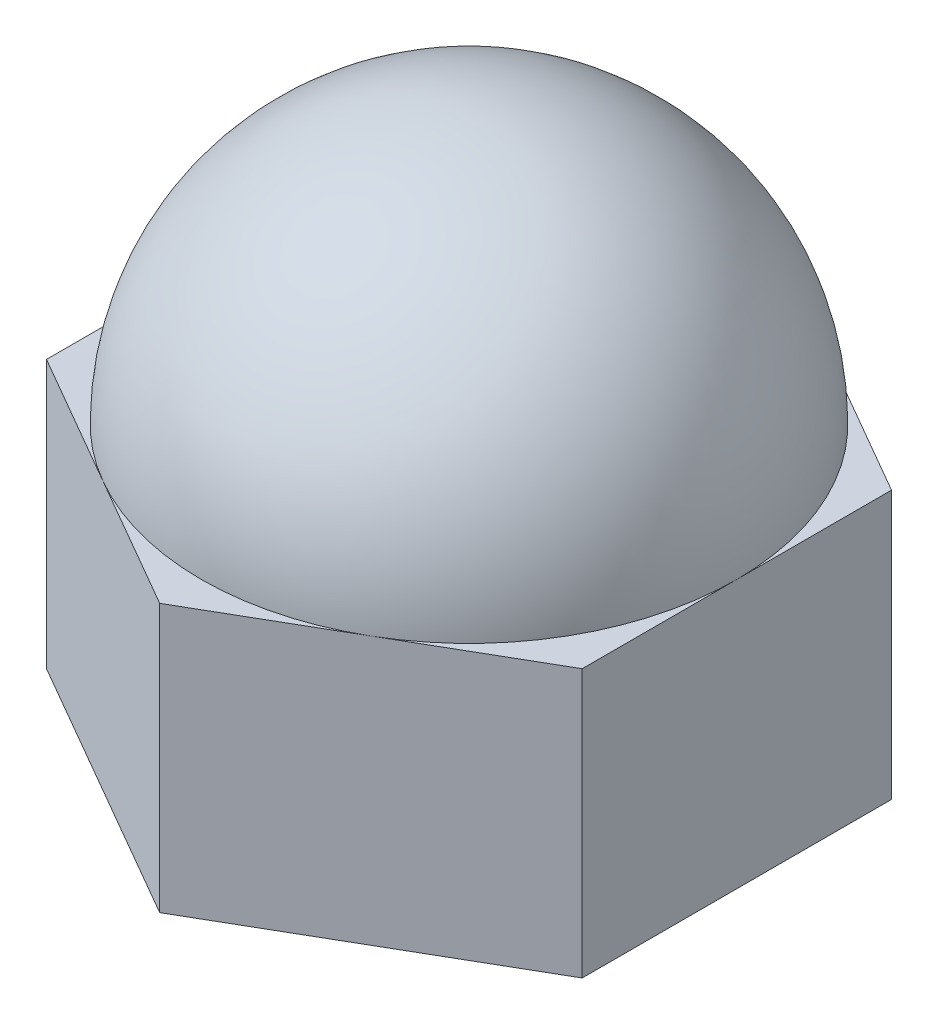
SolidWorks part; units mm, degrees
ref_plane "正面" through (0, 0, 0) normal (0, 0, 1) x (1, 0, 0)
ref_plane "平面" through (0, 0, 0) normal (0, 1, 0) x (1, 0, 0)
ref_plane "右側面" through (0, 0, 0) normal (1, 0, 0) x (0, 0, -1)
sketch "ｽｹｯﾁ1" plane through (0, 0, 0) normal (0, 1, 0) x (1, 0, 0)
  line L1 (0, -7.5056) -> (6.5, -3.7528)
  line L2 (6.5, -3.7528) -> (6.5, 3.7528)
  line L3 (6.5, 3.7528) -> (0, 7.5056)
  line L4 (0, 7.5056) -> (-6.5, 3.7528)
  line L5 (-6.5, 3.7528) -> (-6.5, -3.7528)
  line L6 (-6.5, -3.7528) -> (0, -7.5056)
  circle A0 centre (0, 0) radius 6.5 construction
  dimension "D1" = 13
extrude "ﾎﾞｽ - 押し出し1" add sketch "ｽｹｯﾁ1" along normal blind 6.5
sketch "ｽｹｯﾁ5" plane through (0, 0, 0) normal (0, 0, 1) x (1, 0, 0)
  line L0 (0, 13) -> (0, 6.5)
  line L1 (0, 6.5) -> (6.5, 6.5)
  arc A0 (6.5, 6.5) -> (0, 13) centre (0, 6.5) ccw
revolve "回転1" add sketch "ｽｹｯﾁ5" angle 360 about L0
sketch "ｽｹｯﾁ6" plane through (0, 0, 0) normal (0, -1, 0) x (1, 0, 0)
  circle A0 centre (0, 0) radius 4
  dimension "D1" = 8
extrude "ｶｯﾄ - 押し出し1" cut sketch "ｽｹｯﾁ6" against normal blind 6.5
